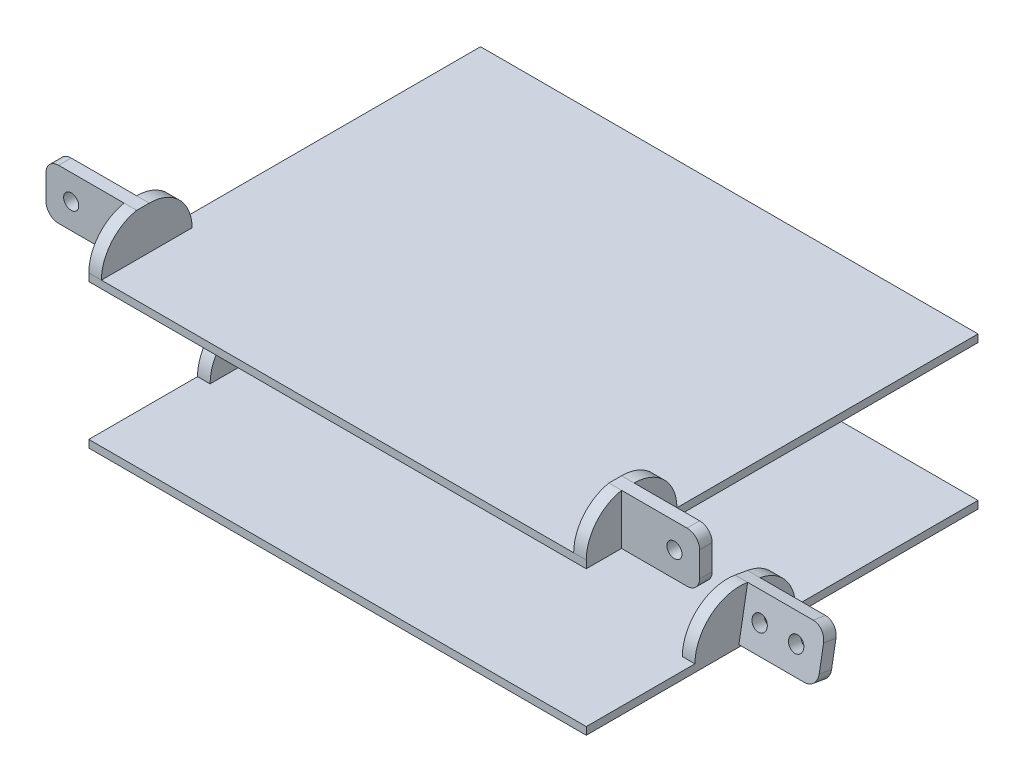
SolidWorks part; units mm, degrees
ref_plane "Front Plane" through (0, 0, 0) normal (0, 0, 1) x (1, 0, 0)
ref_plane "Top Plane" through (0, 0, 0) normal (0, 1, 0) x (1, 0, 0)
ref_plane "Right Plane" through (0, 0, 0) normal (1, 0, 0) x (0, 0, -1)
sketch "Sketch3" plane through (0, 0, 0) normal (0, 0, 1) x (1, 0, 0)
  line L0 (-76.2993, 0) -> (18.6887, 0)
ref_plane "Lower tab plane" through (0, 0, 0) normal (0, 0.1736, 0.9848) x (1, 0, 0)
sketch "Sketch1" plane through (0, 0, 0) normal (0, 0.1736, 0.9848) x (1, 0, 0)
  line L1 (-124.75, 10) -> (-93.75, 10)
  line L2 (-129.75, 5) -> (-129.75, -5)
  line L3 (-124.75, -10) -> (-93.75, -10)
  line L4 (-93.75, 10) -> (-93.75, -10)
  circle A0 centre (-119.75, 0) radius 3
  circle A1 centre (-105.25, 0) radius 3
  arc A2 (-129.75, -5) -> (-124.75, -10) centre (-124.75, -5) ccw
  arc A3 (-124.75, 10) -> (-129.75, 5) centre (-124.75, 5) ccw
  point P4 (-93.75, 0)
  point P18 (-129.75, 10)
  dimension "D4" = 6
  dimension "D5" = 6
  dimension "D8" = 5
  dimension "D1" = 36
  dimension "D2" = 20
  dimension "D3" = 119.75
  dimension "D6" = 14.5
  dimension "D7" = 10
extrude "Lower left tab" add sketch "Sketch1" along normal blind 5
sketch "Sketch2" plane through (-93.75, 0, 0) normal (1, 0, 0) x (0, 0, -1)
  line L1 (-68.7365, -6.8481) -> (88.2635, -6.8481)
  line L2 (-68.7365, -6.8481) -> (-68.7365, -9.8481)
  line L3 (-68.7365, -9.8481) -> (88.2635, -9.8481)
  line L4 (88.2635, -6.8481) -> (88.2635, -9.8481)
  dimension "D1" = 3
  dimension "D2" = 90
  dimension "D3" = 67
extrude "Bottom plate extrude" add sketch "Sketch2" along normal blind 93.75 and the other way blind 5
sketch "Sketch4" plane through (-93.75, 0, 0) normal (1, 0, 0) x (0, 0, -1)
  line L0 (88.2635, -6.8481) -> (-68.7365, -6.8481) construction
  line L1 (15.7462, -6.8481) -> (-1.2075, -6.8481)
  line L2 (-6.2846, -6.8481) -> (-3.1876, 10.7163) construction
  line L3 (-1.2075, -6.8481) -> (1.7365, 9.8481) construction
  line L4 (-6.2846, -6.8481) -> (-3.1876, 10.7163)
  line L5 (-1.2075, -6.8481) -> (1.7365, 9.8481)
  line L6 (-6.2846, -6.8481) -> (-24.12, -6.8481)
  line L7 (-3.1876, 10.7163) -> (1.7365, 9.8481) construction
  arc A0 (1.7365, 9.8481) -> (15.7462, -6.8481) centre (-1.2075, -6.8481) cw
  arc A1 (-3.1876, 10.7163) -> (-24.12, -6.8481) centre (-6.2846, -6.8481) ccw
extrude "Bottom tab support extrude" add sketch "Sketch4" against normal blind 5
ref_plane "Plane2" through (0, 0, -1.7365) normal (0, 0, 1) x (1, 0, 0)
ref_plane "Top tab plane" through (0, 0, 48.2635) normal (0, 0, 1) x (1, 0, 0)
sketch "Sketch5" plane through (0, 0, 48.2635) normal (0, 0, 1) x (1, 0, 0)
  line L0 (-129.75, 5.7923) -> (-129.75, -4.0558) construction
  line L1 (-124.75, 67.4019) -> (-93.75, 67.4019)
  line L2 (-129.75, 62.4019) -> (-129.75, 52.4019)
  line L3 (-124.75, 47.4019) -> (-93.75, 47.4019)
  line L4 (-93.75, 67.4019) -> (-93.75, 47.4019)
  line L5 (-93.75, -6.8481) -> (-93.75, 10.9873) construction
  arc A0 (-129.75, 52.4019) -> (-124.75, 47.4019) centre (-124.75, 52.4019) ccw
  arc A1 (-124.75, 67.4019) -> (-129.75, 62.4019) centre (-124.75, 62.4019) ccw
  circle A2 centre (-119.75, 57.4019) radius 3
  ellipse E0 centre (-119.75, 0.8682) end of major axis (-116.75, 0.8682) minor radius 2.9544 construction
  ellipse E1 centre (-119.75, 0.8682) end of major axis (-116.75, 0.8682) minor radius 2.9544 construction
  point P28 (-93.75, 57.4019)
  dimension "D2" = 5
  dimension "D3" = 6
  dimension "D1" = 20
  dimension "D4" = 67.25
extrude "Top tab extrude" add sketch "Sketch5" along normal blind 5 separate body
sketch "Sketch6" plane through (-93.75, 0, 0) normal (1, 0, 0) x (0, 0, -1)
  line L0 (-53.2635, 47.4019) -> (-48.2635, 47.4019) construction
  line L1 (-67.2635, 47.4019) -> (88.2635, 47.4019)
  line L2 (-67.2635, 47.4019) -> (-67.2635, 50.4019)
  line L3 (-67.2635, 50.4019) -> (88.2635, 50.4019)
  line L4 (88.2635, 47.4019) -> (88.2635, 50.4019)
  line L5 (-48.2635, 47.4019) -> (-48.2635, 67.4019) construction
  line L6 (88.2635, -9.8481) -> (88.2635, -6.8481) construction
  dimension "D1" = 3
  dimension "D2" = 19
extrude "Top plate extrude" add sketch "Sketch6" against normal blind 5 and the other way up to surface (93.75 mm away) other way up to face at (0, -8.3481, -9.7635)
sketch "Sketch7" plane through (-93.75, 0, 0) normal (1, 0, 0) x (0, 0, -1)
  line L0 (-48.2635, 50.4019) -> (-48.2635, 67.4019) construction
  line L1 (88.2635, 50.4019) -> (-67.2635, 50.4019) construction
  line L2 (-53.2635, 50.4019) -> (-53.2635, 67.4019) construction
  line L3 (-48.2635, 50.4019) -> (-48.2635, 67.4019)
  line L4 (-31.2635, 50.4019) -> (-48.2635, 50.4019)
  line L5 (-53.2635, 50.4019) -> (-53.2635, 67.4019)
  line L6 (-53.2635, 50.4019) -> (-67.2635, 50.4019)
  line L7 (-67.2635, 50.4019) -> (-67.2635, 47.4019) construction
  arc A0 (-67.2635, 50.4019) -> (-53.2635, 67.4019) centre (-49.9421, 50.4019) cw
  arc A1 (-48.2635, 67.4019) -> (-31.2635, 50.4019) centre (-48.2635, 50.4019) cw
extrude "Top tab support extrude" add sketch "Sketch7" against normal blind 5
mirror "Mirror" about plane through (0, 0, 0) normal (1, 0, 0) of "Top tab extrude", "Top plate extrude", "Top tab support extrude", "Lower left tab", "Bottom plate extrude", "Bottom tab support extrude"
ref_plane "Split plane" through (0, 30, 0) normal (0, 1, 0) x (1, 0, 0)
split "Split1" trim tools "Split plane" bodies to split 109 110 resulting bodies 107 108
sketch "Sketch8" plane through (0, -6.8481, 0) normal (0, 1, 0) x (1, 0, 0)
  line L0 (-98.75, -67.2635) -> (-98.75, -68.7365)
  line L1 (-98.75, -68.7365) -> (98.75, -68.7365)
  line L2 (98.75, -68.7365) -> (98.75, -67.2635)
  line L3 (98.75, -24.12) -> (98.75, -68.7365) construction
  line L4 (98.75, -67.2635) -> (98.75, -53.2635) construction
  line L5 (98.75, -67.2635) -> (-98.75, -67.2635)
extrude "Bottom plate was too long" cut sketch "Sketch8" against normal blind 10
